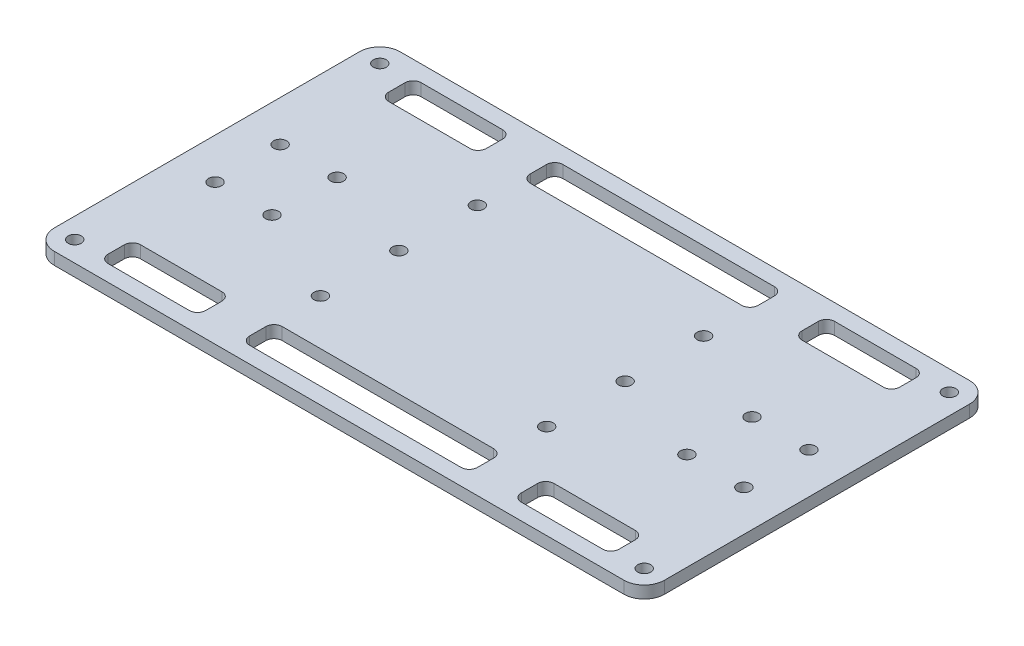
SolidWorks part; units mm, degrees
ref_plane "Front Plane" through (0, 0, 0) normal (0, 0, 1) x (1, 0, 0)
ref_plane "Top Plane" through (0, 0, 0) normal (0, 1, 0) x (1, 0, 0)
ref_plane "Right Plane" through (0, 0, 0) normal (1, 0, 0) x (0, 0, -1)
sketch "Sketch1" plane through (0, 0, 0) normal (0, 1, 0) x (1, 0, 0)
  line L0 (-75, 0) -> (75, 0) construction
  line L1 (-70, 42.5) -> (70, 42.5)
  line L2 (-75, 37.5) -> (-75, -37.5)
  line L3 (-70, -42.5) -> (70, -42.5)
  line L4 (75, 37.5) -> (75, -37.5)
  line L5 (-75, 42.5) -> (75, -42.5) construction
  line L6 (-75, -42.5) -> (75, 42.5) construction
  line L7 (0, 42.5) -> (0, -42.5) construction
  line L8 (-65, 8) -> (-65, -8) construction
  line L9 (-58, 8) -> (-58, -8) construction
  line L10 (58, 8) -> (58, -8) construction
  line L11 (65, 8) -> (65, -8) construction
  line L12 (-27.81, 42.5) -> (-27.81, -42.5) construction
  line L13 (27.81, -19.29) -> (-27.81, -19.29) construction
  line L14 (28, 32.5) -> (28, 36.5)
  line L15 (-26, -30.5) -> (26, -30.5)
  line L16 (-28, -32.5) -> (-28, -36.5)
  line L17 (-26, -38.5) -> (26, -38.5)
  line L18 (28, -32.5) -> (28, -36.5)
  line L19 (-28, -30.5) -> (28, -38.5) construction
  line L20 (-28, -38.5) -> (28, -30.5) construction
  line L21 (-26, 38.5) -> (26, 38.5)
  line L22 (-28, 32.5) -> (-28, 36.5)
  line L23 (-26, 30.5) -> (26, 30.5)
  line L24 (-50.81, 42.5) -> (-50.81, -42.5) construction
  line L25 (-38.81, 32.5) -> (-38.81, 36.5)
  line L26 (-60.81, -30.5) -> (-40.81, -30.5)
  line L27 (-62.81, -32.5) -> (-62.81, -36.5)
  line L28 (-60.81, -38.5) -> (-40.81, -38.5)
  line L29 (-38.81, -32.5) -> (-38.81, -36.5)
  line L30 (-62.81, -30.5) -> (-38.81, -38.5) construction
  line L31 (-62.81, -38.5) -> (-38.81, -30.5) construction
  line L32 (-60.81, 38.5) -> (-40.81, 38.5)
  line L33 (-62.81, 32.5) -> (-62.81, 36.5)
  line L34 (-60.81, 30.5) -> (-40.81, 30.5)
  line L35 (38.81, 32.5) -> (38.81, 36.5)
  line L36 (60.81, 30.5) -> (40.81, 30.5)
  line L37 (62.81, 32.5) -> (62.81, 36.5)
  line L38 (60.81, 38.5) -> (40.81, 38.5)
  line L39 (38.81, -32.5) -> (38.81, -36.5)
  line L40 (60.81, -38.5) -> (40.81, -38.5)
  line L41 (62.81, -32.5) -> (62.81, -36.5)
  line L42 (60.81, -30.5) -> (40.81, -30.5)
  arc A0 (70, -42.5) -> (75, -37.5) centre (70, -37.5) ccw
  arc A1 (75, 37.5) -> (70, 42.5) centre (70, 37.5) ccw
  arc A2 (-70, -42.5) -> (-75, -37.5) centre (-70, -37.5) cw
  arc A3 (-75, 37.5) -> (-70, 42.5) centre (-70, 37.5) cw
  circle A4 centre (-65, 8) radius 1.6
  circle A5 centre (-65, -8) radius 1.6
  circle A6 centre (-51, 8) radius 1.6
  circle A7 centre (-51, -8) radius 1.6
  circle A8 centre (51, -8) radius 1.6
  circle A9 centre (51, 8) radius 1.6
  circle A10 centre (65, -8) radius 1.6
  circle A11 centre (65, 8) radius 1.6
  circle A12 centre (-27.81, 19.29) radius 1.6
  circle A13 centre (-27.81, 0) radius 1.6
  circle A14 centre (-27.81, -19.29) radius 1.6
  circle A15 centre (27.81, -19.29) radius 1.6
  circle A16 centre (27.81, 19.29) radius 1.6
  circle A17 centre (27.81, 0) radius 1.6
  arc A18 (-26, -30.5) -> (-28, -32.5) centre (-26, -32.5) ccw
  arc A19 (-28, -36.5) -> (-26, -38.5) centre (-26, -36.5) ccw
  arc A20 (26, -38.5) -> (28, -36.5) centre (26, -36.5) ccw
  arc A21 (28, -32.5) -> (26, -30.5) centre (26, -32.5) ccw
  arc A22 (26, 38.5) -> (28, 36.5) centre (26, 36.5) cw
  arc A23 (28, 32.5) -> (26, 30.5) centre (26, 32.5) cw
  arc A24 (-28, 36.5) -> (-26, 38.5) centre (-26, 36.5) cw
  arc A25 (-26, 30.5) -> (-28, 32.5) centre (-26, 32.5) cw
  arc A26 (-60.81, -30.5) -> (-62.81, -32.5) centre (-60.81, -32.5) ccw
  arc A27 (-62.81, -36.5) -> (-60.81, -38.5) centre (-60.81, -36.5) ccw
  arc A28 (-40.81, -38.5) -> (-38.81, -36.5) centre (-40.81, -36.5) ccw
  arc A29 (-38.81, -32.5) -> (-40.81, -30.5) centre (-40.81, -32.5) ccw
  arc A30 (-38.81, 32.5) -> (-40.81, 30.5) centre (-40.81, 32.5) cw
  arc A31 (-40.81, 38.5) -> (-38.81, 36.5) centre (-40.81, 36.5) cw
  arc A32 (-62.81, 36.5) -> (-60.81, 38.5) centre (-60.81, 36.5) cw
  arc A33 (-60.81, 30.5) -> (-62.81, 32.5) centre (-60.81, 32.5) cw
  arc A34 (40.81, 38.5) -> (38.81, 36.5) centre (40.81, 36.5) ccw
  arc A35 (38.81, 32.5) -> (40.81, 30.5) centre (40.81, 32.5) ccw
  arc A36 (60.81, 30.5) -> (62.81, 32.5) centre (60.81, 32.5) ccw
  arc A37 (62.81, 36.5) -> (60.81, 38.5) centre (60.81, 36.5) ccw
  arc A38 (38.81, -32.5) -> (40.81, -30.5) centre (40.81, -32.5) cw
  arc A39 (40.81, -38.5) -> (38.81, -36.5) centre (40.81, -36.5) cw
  arc A40 (62.81, -36.5) -> (60.81, -38.5) centre (60.81, -36.5) cw
  arc A41 (60.81, -30.5) -> (62.81, -32.5) centre (60.81, -32.5) cw
  circle A42 centre (-70, 37.5) radius 1.6
  circle A43 centre (-70, -37.5) radius 1.6
  circle A44 centre (70, -37.5) radius 1.6
  circle A45 centre (70, 37.5) radius 1.6
  point P0 (0, 0)
  point P56 (0, -34.5)
  point P87 (-50.81, -34.5)
  dimension "D3" = 5
  dimension "D4" = 3.2
  dimension "D7" = 7
  dimension "D9" = 3.2
  dimension "D10" = 3.2
  dimension "D15" = 2
  dimension "D20" = 2
  dimension "D21" = 3.2
  dimension "D1" = 85
  dimension "D2" = 150
  dimension "D5" = 10
  dimension "D6" = 8
  dimension "D11" = 19.29
  dimension "D12" = 8
  dimension "D13" = 8
  dimension "D14" = 56
  dimension "D16" = 23
  dimension "D17" = 24
  dimension "D18" = 8
  dimension "D19" = 8
  dimension "D8" = 27.81
extrude "Boss-Extrude1" add sketch "Sketch1" along normal blind 3
